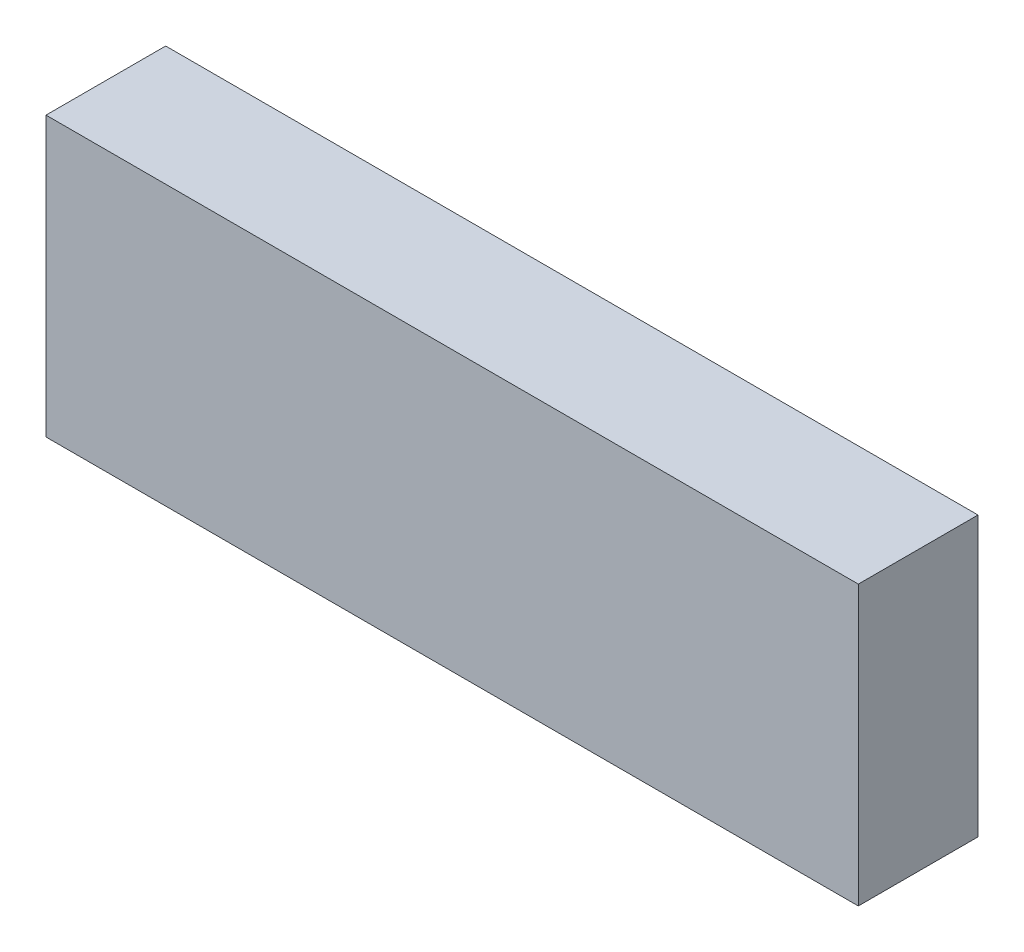
SolidWorks part; units mm, degrees
ref_plane "Front Plane" through (0, 0, 0) normal (0, 0, 1) x (1, 0, 0)
ref_plane "Top Plane" through (0, 0, 0) normal (0, 1, 0) x (1, 0, 0)
ref_plane "Right Plane" through (0, 0, 0) normal (1, 0, 0) x (0, 0, -1)
sketch "Sketch1" plane through (0, 0, 0) normal (0, 0, 1) x (1, 0, 0)
  line L1 (0, 0) -> (67.8688, 0)
  line L2 (0, 0) -> (0, -23.2918)
  line L3 (0, -23.2918) -> (67.8688, -23.2918)
  line L4 (67.8688, 0) -> (67.8688, -23.2918)
  dimension "D1" = 67.8688
  dimension "D2" = 23.2918
extrude "Boss-Extrude1" add sketch "Sketch1" along normal blind 10
